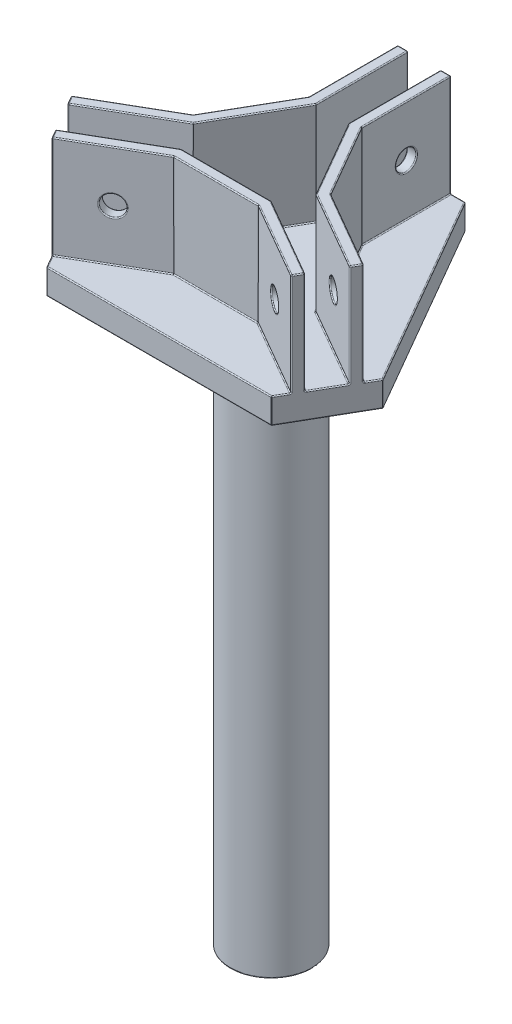
SolidWorks part; units mm, degrees
ref_plane "Alzado" through (0, 0, 0) normal (0, 0, 1) x (1, 0, 0)
ref_plane "Planta" through (0, 0, 0) normal (0, 1, 0) x (1, 0, 0)
ref_plane "Vista lateral" through (0, 0, 0) normal (1, 0, 0) x (0, 0, -1)
sketch "Croquis1" plane through (0, 0, 0) normal (0, 1, 0) x (1, 0, 0)
  line L0 (0, 0) -> (-13, -7.5056) construction
  line L1 (0, 0) -> (0, 15.0111) construction
  line L2 (0, 0) -> (13, -7.5056) construction
  line L3 (-4, 15.0111) -> (4, 15.0111)
  line L4 (15, -4.0415) -> (11, -10.9697)
  line L5 (-15, -4.0415) -> (-11, -10.9697)
  line L6 (-4, 15.0111) -> (-15, -4.0415)
  line L7 (4, 15.0111) -> (15, -4.0415)
  line L8 (11, -10.9697) -> (-11, -10.9697)
  point P11 (0, 15.0111)
  point P12 (-13, -7.5056)
  point P13 (13, -7.5056)
  dimension "D1" = 120
  dimension "D2" = 120
  dimension "D3" = 8
  dimension "D4" = 22
extrude "Saliente-Extruir1" add sketch "Croquis1" along normal blind 2.5
sketch "Croquis2" plane through (0, 2.5, 0) normal (0, 1, 0) x (1, 0, 0)
  line L0 (-13, -7.5056) -> (0, 0) construction
  line L1 (-15, -4.0415) -> (-11, -10.9697) construction
  line L2 (0, 0) -> (13, -7.5056) construction
  line L3 (11, -10.9697) -> (15, -4.0415) construction
  line L4 (0, 15.0111) -> (0, 0) construction
  line L5 (4, 15.0111) -> (-4, 15.0111) construction
  line L6 (-12.2, -8.8912) -> (-4.4058, -4.3912)
  line L7 (-4.4058, -4.3912) -> (4.4058, -4.3912)
  line L8 (4.4058, -4.3912) -> (12.2, -8.8912)
  line L9 (-11.7, -9.7572) -> (-4.1378, -5.3912)
  line L10 (-4.1378, -5.3912) -> (4.1378, -5.3912)
  line L11 (4.1378, -5.3912) -> (11.7, -9.7572)
  line L12 (-12.2, -8.8912) -> (-11.7, -9.7572)
  line L13 (12.2, -8.8912) -> (11.7, -9.7572)
  line L14 (-1.6, 15.0111) -> (-1.6, 6.0111)
  line L15 (-2.6, 15.0111) -> (-2.6, 6.2791)
  line L16 (-1.6, 15.0111) -> (-2.6, 15.0111)
  line L17 (-1.6, 6.0111) -> (-6.0058, -1.6199)
  line L18 (-2.6, 6.2791) -> (-6.7378, -0.8879)
  line L19 (-6.0058, -1.6199) -> (-13.8, -6.1199)
  line L20 (-6.7378, -0.8879) -> (-14.3, -5.2539)
  line L21 (-13.8, -6.1199) -> (-14.3, -5.2539)
  line L22 (13.8, -6.1199) -> (6.0058, -1.6199)
  line L23 (14.3, -5.2539) -> (6.7378, -0.8879)
  line L24 (13.8, -6.1199) -> (14.3, -5.2539)
  line L25 (6.0058, -1.6199) -> (1.6, 6.0111)
  line L26 (6.7378, -0.8879) -> (2.6, 6.2791)
  line L27 (1.6, 6.0111) -> (1.6, 15.0111)
  line L28 (2.6, 6.2791) -> (2.6, 15.0111)
  line L29 (1.6, 15.0111) -> (2.6, 15.0111)
  circle A0 centre (0, 0) radius 4 construction
  point P14 (0, -4.3912)
  point P40 (0, 0)
  dimension "D1" = 8
  dimension "D2" = 1.6
  dimension "D3" = 9
  dimension "D4" = 1
  dimension "D5" = 3
extrude "Saliente-Extruir2" add sketch "Croquis2" along normal blind 10
sketch "Croquis3" plane through (0, 0, 0) normal (0, -1, 0) x (1, 0, 0)
  circle A0 centre (0, 0) radius 4 construction
  circle A1 centre (0, 0) radius 4
extrude "Saliente-Extruir3" add sketch "Croquis3" along normal blind 55
sketch "Croquis5" plane through (-1.3, 0, -2.2517) normal (-0.5, 0, -0.866) x (-0.866, 0, 0.5)
  line L0 (6.2791, 7.5) -> (15.0111, 7.5) construction
  line L1 (6.2791, 12.5) -> (6.2791, 2.5) construction
  line L2 (15.0111, 12.5) -> (15.0111, 2.5) construction
  circle A0 centre (10.6451, 7.5) radius 1
  dimension "D1" = 2
extrude "Cortar-Extruir1" cut sketch "Croquis5" against normal through all
pattern_circular "MatrizC1" count 3 over 360 about axis through (0, -55, 0) along (0, 1, 0) of "Cortar-Extruir1"
fillet "Redondeo1" radius 0.1 104 edges at (8.7849, 7.5, 8.0742) (2.6, 7.5, -11.6451) (9.1529, 7.5, 3.4369) (11.3849, 7.5, 3.5709) (9.2849, 7.5, 7.2082) (1.6, 7.5, -11.6451) (-1.6, 7.5, -9.6451) (-2.6, 7.5, -11.6451) (-11.3849, 7.5, 3.5709) (-10.8849, 7.5, 4.4369) (-7.5529, 7.5, 6.2082) (-8.7849, 7.5, 8.0742) (14.3, 7.5, 5.2539) (6.7378, 7.5, 0.8879) (2.6, 7.5, -6.2791) (2.6, 7.5, -15.0111) (1.6, 7.5, -15.0111) (1.6, 7.5, -6.0111) (6.0058, 7.5, 1.6199) (13.8, 7.5, 6.1199) (9.9029, 12.5, 3.8699) (3.8029, 12.5, -2.1956) (1.6, 12.5, -10.5111) (2.1, 12.5, -15.0111) (2.6, 12.5, -10.6451) (4.6689, 12.5, -2.6956) (10.5189, 12.5, 3.0709) (14.05, 12.5, 5.6869) (9.9029, 2.5, 3.8699) (3.8029, 2.5, -2.1956) (1.6, 2.5, -10.5111) (2.6, 2.5, -10.6451) (4.6689, 2.5, -2.6956) (10.5189, 2.5, 3.0709) (-2.6, 7.5, -15.0111) (-2.6, 7.5, -6.2791) (-6.7378, 7.5, 0.8879) (-14.3, 7.5, 5.2539) (-13.8, 7.5, 6.1199) (-6.0058, 7.5, 1.6199) (-1.6, 7.5, -6.0111) (-1.6, 7.5, -15.0111) (-1.6, 12.5, -10.5111) (-3.8029, 12.5, -2.1956) (-9.9029, 12.5, 3.8699) (-14.05, 12.5, 5.6869) (-10.5189, 12.5, 3.0709) (-4.6689, 12.5, -2.6956) (-2.6, 12.5, -10.6451) (-2.1, 12.5, -15.0111) (-1.6, 2.5, -10.5111) (-3.8029, 2.5, -2.1956) (-9.9029, 2.5, 3.8699) (-10.5189, 2.5, 3.0709) (-4.6689, 2.5, -2.6956) (-2.6, 2.5, -10.6451) (-7.9189, 2.5, 7.5742) (0, 2.5, 5.3912) (7.9189, 2.5, 7.5742) (8.3029, 2.5, 6.6412) (0, 2.5, 4.3912) (-8.3029, 2.5, 6.6412) (-11.95, 12.5, 9.3242) (-7.9189, 12.5, 7.5742) (0, 12.5, 5.3912) (7.9189, 12.5, 7.5742) (11.95, 12.5, 9.3242) (8.3029, 12.5, 6.6412) (0, 12.5, 4.3912) (-8.3029, 12.5, 6.6412) (-12.2, 7.5, 8.8912) (-4.4058, 7.5, 4.3912) (4.4058, 7.5, 4.3912) (12.2, 7.5, 8.8912) (11.7, 7.5, 9.7572) (4.1378, 7.5, 5.3912) (-4.1378, 7.5, 5.3912) (-11.7, 7.5, 9.7572) (-9.5, 0, -5.4848) (-13, 0, 7.5056) (0, 0, 10.9697) (13, 0, 7.5056) (9.5, 0, -5.4848) (0, 0, -15.0111) (-9.5, 2.5, -5.4848) (-11.35, 2.5, 10.3634) (-13, 2.5, 7.5056) (-14.65, 2.5, 4.6477) (0, 2.5, 10.9697) (14.65, 2.5, 4.6477) (13, 2.5, 7.5056) (11.35, 2.5, 10.3634) (9.5, 2.5, -5.4848) (-3.3, 2.5, -15.0111) (0, 2.5, -15.0111) (3.3, 2.5, -15.0111) (-4, 1.25, -15.0111) (4, 1.25, -15.0111) (15, 1.25, 4.0415) (11, 1.25, 10.9697) (-11, 1.25, 10.9697) (-15, 1.25, 4.0415) (0, 0, -4) (0, -55, -4)
